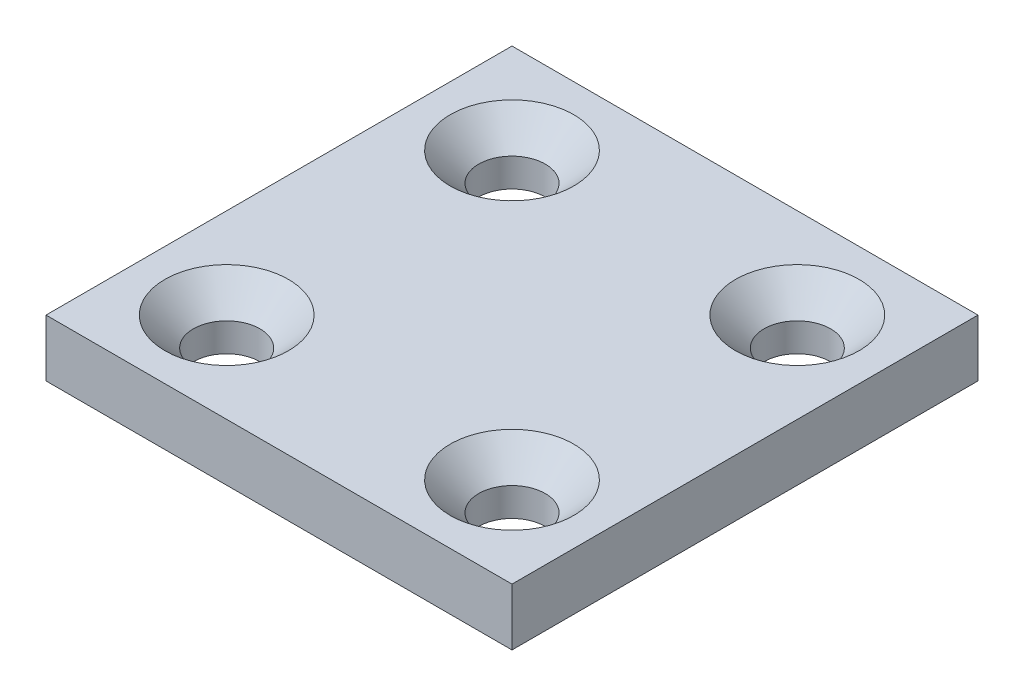
SolidWorks part; units mm, degrees
ref_plane "前视基准面" through (0, 0, 0) normal (0, 0, 1) x (1, 0, 0)
ref_plane "上视基准面" through (0, 0, 0) normal (0, 1, 0) x (1, 0, 0)
ref_plane "右视基准面" through (0, 0, 0) normal (1, 0, 0) x (0, 0, -1)
sketch "草图1" plane through (0, 0, 0) normal (0, 1, 0) x (1, 0, 0)
  line L1 (-4.75, -4.75) -> (19.75, -4.75)
  line L2 (-4.75, -4.75) -> (-4.75, 19.75)
  line L3 (-4.75, 19.75) -> (19.75, 19.75)
  line L4 (19.75, -4.75) -> (19.75, 19.75)
  circle A0 centre (0, 0) radius 1.75
  circle A1 centre (15, 0) radius 1.75
  circle A2 centre (0, 15) radius 1.75
  circle A3 centre (15, 15) radius 1.75
  dimension "D2" = 3.5
  dimension "D3" = 3.5
  dimension "D5" = 3.5
  dimension "D6" = 3.5
  dimension "D10" = 4.75
  dimension "D1" = 15
  dimension "D4" = 15
  dimension "D7" = 15
  dimension "D8" = 24.5
  dimension "D9" = 24.5
  dimension "D11" = 4.75
extrude "凸台-拉伸1" add sketch "草图1" along normal blind 3
hole_wizard "M3 平头机械螺钉的锥形沉头孔1" positions "草图4" profile "草图5" countersink size "M3" standard "ANSI Metric" end condition up to next
sketch "草图4" plane through (0, 3, 0) normal (0, 1, 0) x (1, 0, 0)
  point P0 (0, 0)
  point P3 (15, 0)
  point P6 (15, 15)
  point P9 (0, 15)
sketch "草图5" plane through (0, 3, 0) normal (1, 0, 0) x (0, 0, 1)
  line L0 (0, 0) -> (0, 3)
  line L1 (0, 3) -> (1.6, 3)
  line L2 (1.6, 3) -> (1.6, 1.65)
  line L3 (1.6, 1.65) -> (3.25, 0)
  line L5 (3.25, 0) -> (0, 0)
  line L6 (-1.6, 1.65) -> (-3.25, 0) construction
  line L11 (0, -6.35) -> (0, 107.95) construction
  dimension "通孔孔直径" = 3.2
  dimension "通孔孔深度" = 3
  dimension "近端锥形沉头孔直径" = 6.5
  dimension "近端锥形沉头孔角度" = 90
